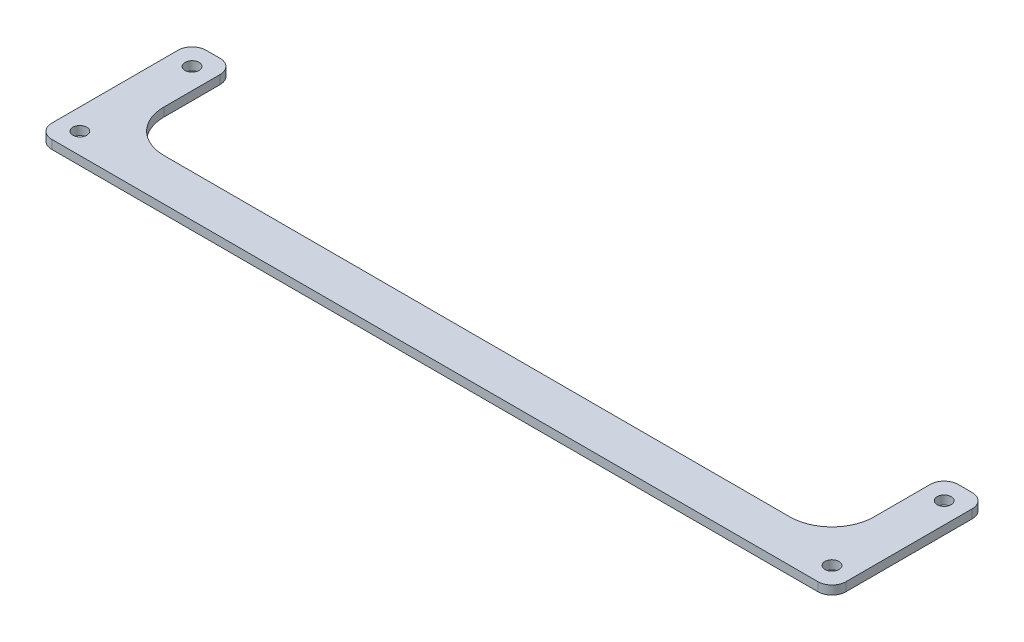
SolidWorks part; units mm, degrees
ref_plane "Front Plane" through (0, 0, 0) normal (0, 0, 1) x (1, 0, 0)
ref_plane "Top Plane" through (0, 0, 0) normal (0, 1, 0) x (1, 0, 0)
ref_plane "Right Plane" through (0, 0, 0) normal (1, 0, 0) x (0, 0, -1)
sketch "Sketch1" plane through (0, 0, 0) normal (0, 1, 0) x (1, 0, 0)
  line L0 (-20.7988, 2.8691) -> (-20.7988, -29.1309) construction
  line L2 (-20.7988, 2.8691) -> (-14.7988, 2.8691) construction
  line L4 (-20.7988, -29.1309) -> (193.6657, -29.1309) construction
  line L5 (193.6657, 2.8691) -> (193.6657, -29.1309) construction
  line L7 (-14.7988, 8.8691) -> (-26.7988, 8.8691)
  line L8 (199.6657, -35.1309) -> (-26.7988, -35.1309)
  line L9 (199.6657, -35.1309) -> (199.6657, 8.8691)
  line L10 (199.6657, 8.8691) -> (187.6657, 8.8691)
  line L11 (-26.7988, -35.1309) -> (-26.7988, 8.8691)
  line L94 (-14.7988, 8.8691) -> (-14.7988, -23.1309)
  line L95 (187.6657, 8.8691) -> (187.6657, -23.1309)
  line L96 (-14.7988, -23.1309) -> (187.6657, -23.1309)
  circle A0 centre (-20.7988, 2.8691) radius 2
  circle A1 centre (-20.7988, -29.1309) radius 2
  circle A2 centre (193.6657, 2.8691) radius 2
  circle A3 centre (193.6657, -29.1309) radius 2
  point P14 (-14.7988, -7.1309)
  point P16 (0, 0)
  point P17 (82.5759, -24.4558)
  point P262 (0, 0)
  dimension "D2" = 4
  dimension "D3" = 4
  dimension "D5" = 4
  dimension "D6" = 4
  dimension "D1" = 32
  dimension "Some" = 214.4646
  dimension "D7" = 6
  dimension "D8" = 6
  dimension "D9" = 12
  dimension "D10" = 12
  dimension "D11" = 6
  dimension "D12" = 12
  dimension "D21" = 32
  dimension "D23" = 32
extrude "Boss-Extrude1" add sketch "Sketch1" along normal blind 2.5
fillet "Fillet1" radius 4 6 edges at (199.6657, 1.25, -8.8691) (199.6657, 1.25, 35.1309) (-26.7988, 1.25, 35.1309) (187.6657, 1.25, -8.8691) (-14.7988, 1.25, -8.8691) (-26.7988, 1.25, -8.8691)
fillet "Fillet3" radius 12 2 edges at (-14.7988, 1.25, 23.1309) (187.6657, 1.25, 23.1309)
